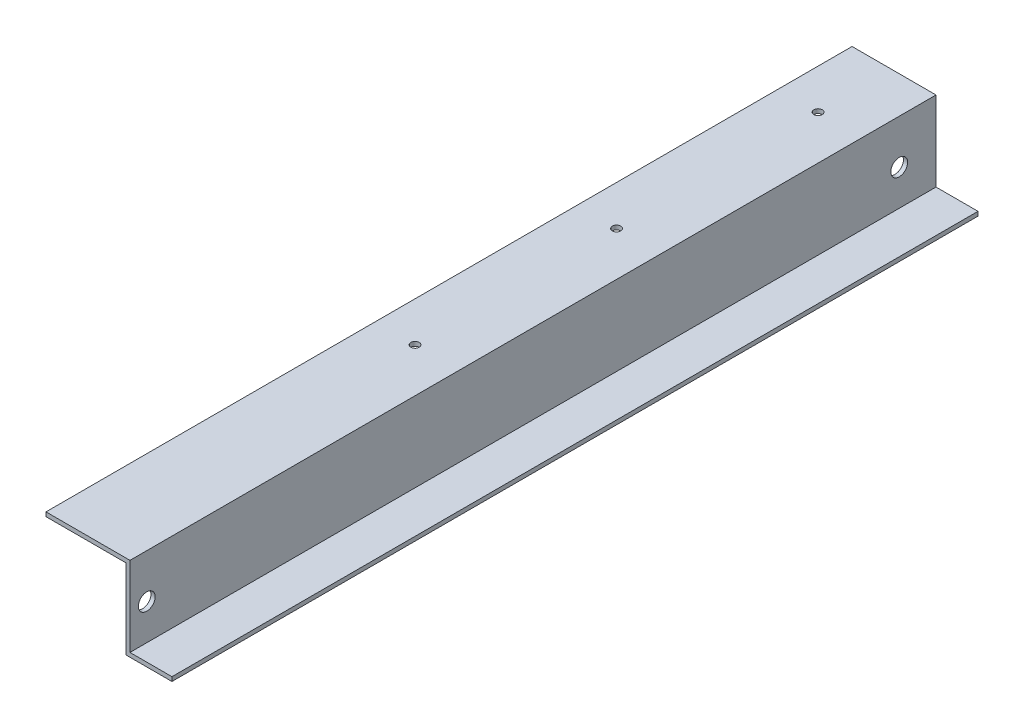
SolidWorks part; units mm, degrees
ref_plane "Front Plane" through (0, 0, 0) normal (0, 0, 1) x (1, 0, 0)
ref_plane "Top Plane" through (0, 0, 0) normal (0, 1, 0) x (1, 0, 0)
ref_plane "Right Plane" through (0, 0, 0) normal (1, 0, 0) x (0, 0, -1)
sketch "Sketch1" plane through (0, 0, 0) normal (0, 0, 1) x (1, 0, 0)
  line L0 (0, -15.0813) -> (0, 15.0813) construction
  line L1 (0, 15.0813) -> (-30.9563, 15.0813) construction
  line L2 (0, -15.0813) -> (30.9563, -15.0812) construction
  line L3 (0.7937, -14.2875) -> (30.9563, -14.2875) construction
  line L4 (0.7937, -14.2875) -> (0.7937, 15.875) construction
  line L5 (0.7937, 15.875) -> (-30.9563, 15.875) construction
  line L6 (-0.7937, -15.875) -> (30.9563, -15.875) construction
  line L7 (-0.7937, -15.875) -> (-0.7937, 14.2875) construction
  line L8 (-0.7937, 14.2875) -> (-30.9563, 14.2875) construction
  line L9 (-30.9563, 15.875) -> (-30.9563, 14.2875) construction
  line L10 (30.9563, -14.2875) -> (30.9563, -15.875) construction
  point P4 (0, 0)
  dimension "Leg Width" = 31.75
  dimension "Outside Height" = 31.75
  dimension "Wall Thickness" = 1.5875
sketch "Sketch2" plane through (0, 0, 0) normal (1, 0, 0) x (0, 0, -1)
  line L0 (152.4, 0) -> (-152.4, 0) construction
  line L1 (0, 0) -> (0, 15.875) construction
  line L2 (-152.4, 0) -> (-152.4, 15.875) construction
  line L3 (152.4, 0) -> (152.4, 15.875) construction
  point P0 (-114.3, 0)
  point P3 (114.3, 0)
  point P4 (0, 0)
  dimension "D1" = 228.6
  dimension "Length" = 304.8
sketch "Sketch3" plane through (0, 0, 0) normal (0, 0, 1) x (1, 0, 0)
  line L3 (-0.7937, -15.875) -> (-0.7937, 14.2875) construction
  line L4 (0.7937, -14.2875) -> (0.7937, 15.875) construction
  line L5 (0.7937, 15.875) -> (-30.9563, 15.875) construction
  line L6 (-30.9563, 15.875) -> (-30.9563, 14.2875) construction
  line L7 (-0.7937, 14.2875) -> (-30.9563, 14.2875) construction
  line L8 (16.6687, -14.2875) -> (16.6687, -15.875)
  line L9 (0.7937, -14.2875) -> (16.6687, -14.2875)
  line L10 (-0.7937, -15.875) -> (16.6687, -15.875)
  line L11 (-0.7937, -15.875) -> (-0.7937, 14.2875)
  line L12 (0.7937, -14.2875) -> (0.7937, 15.875)
  line L13 (0.7937, 15.875) -> (-30.9563, 15.875)
  line L14 (-30.9563, 15.875) -> (-30.9563, 14.2875)
  line L15 (-0.7937, 14.2875) -> (-30.9563, 14.2875)
extrude "Boss-Extrude1" add sketch "Sketch3" along normal up to vertex (152.4 mm away) and the other way up to vertex (152.4 mm away) up to point (0, 0, 152.4) other way up to point (0, 0, -152.4)
sketch "Sketch8" plane through (0, 14.2875, 0) normal (0, -1, 0) x (1, 0, 0)
  line L0 (-0.7937, 152.4) -> (-0.7937, -152.4) construction
  line L2 (-15.875, -152.4) -> (-15.875, -133.35) construction
  line L3 (-30.9563, -152.4) -> (-0.7937, -152.4) construction
  line L4 (-15.875, -133.35) -> (-15.875, -124.46) construction
  line L5 (-15.875, -124.46) -> (-15.875, -48.26) construction
  line L6 (-15.875, -48.26) -> (-15.875, 27.94) construction
  circle A0 centre (-15.875, -124.46) radius 1.5875
  circle A1 centre (-15.875, -48.26) radius 1.5875
  circle A2 centre (-15.875, 27.94) radius 1.5875
  dimension "D1" = 15.0813
extrude "Cut-Extrude1" cut sketch "Sketch8" against normal blind 1.5875
sketch "Sketch9" plane through (-0.7937, 0, 0) normal (-1, 0, 0) x (0, 0, 1)
  line L0 (-152.4, -0.7937) -> (-138.4808, -0.7937) construction
  line L1 (-152.4, 14.2875) -> (-152.4, -15.875) construction
  line L2 (146.05, -0.7937) -> (152.4, -0.7937) construction
  line L3 (152.4, 14.2875) -> (152.4, -15.875) construction
  circle A0 centre (-138.4808, -0.7937) radius 3.175
  circle A1 centre (146.05, -0.7937) radius 3.175
extrude "Cut-Extrude2" cut sketch "Sketch9" against normal blind 1.5875
equation "\"D1@Sketch2\"=\"Length@Sketch2\"*0.75"
